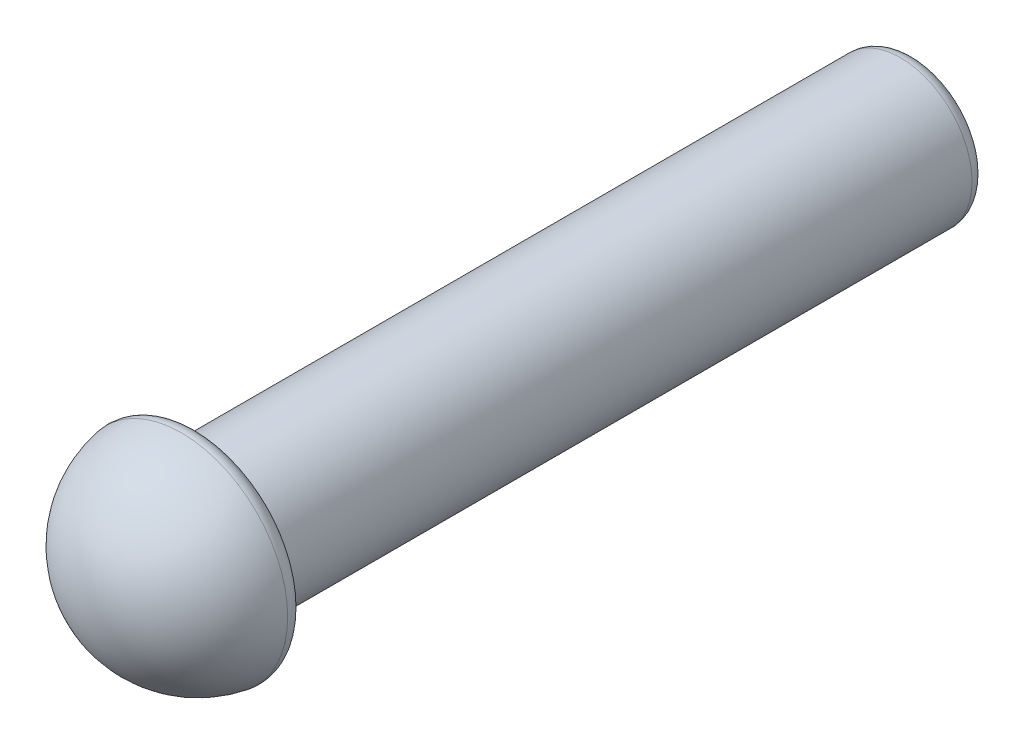
SolidWorks part; units mm, degrees
ref_plane "Front Plane" through (0, 0, 0) normal (0, 0, 1) x (1, 0, 0)
ref_plane "Top Plane" through (0, 0, 0) normal (0, 1, 0) x (1, 0, 0)
ref_plane "Right Plane" through (0, 0, 0) normal (1, 0, 0) x (0, 0, -1)
sketch "Sketch4" plane through (0, 0, 0) normal (1, 0, 0) x (0, 0, -1)
  line L0 (0, 0) -> (25.4, 0) construction
  line L1 (-3.3071, 0) -> (25.4, 0)
  line L2 (25.4, 0) -> (25.4, 2.54)
  line L3 (25.4, 2.54) -> (0, 2.54)
  line L4 (0, 2.54) -> (0, 3.81)
  line L5 (-3.3071, 0) -> (-3.81, 0)
  arc A1 (0, 3.81) -> (-3.81, 0) centre (0, 0) ccw
  dimension "D3" = 3.81
  dimension "D1" = 25.4
  dimension "D2" = 2.54
  dimension "D4" = 3.81
revolve "Revolve4" add sketch "Sketch4" angle 360 about L1
fillet "Fillet1" radius 0.508 3 edges at (2.54, 0, -25.4) (2.54, 0, 0) (3.81, 0, 0)
